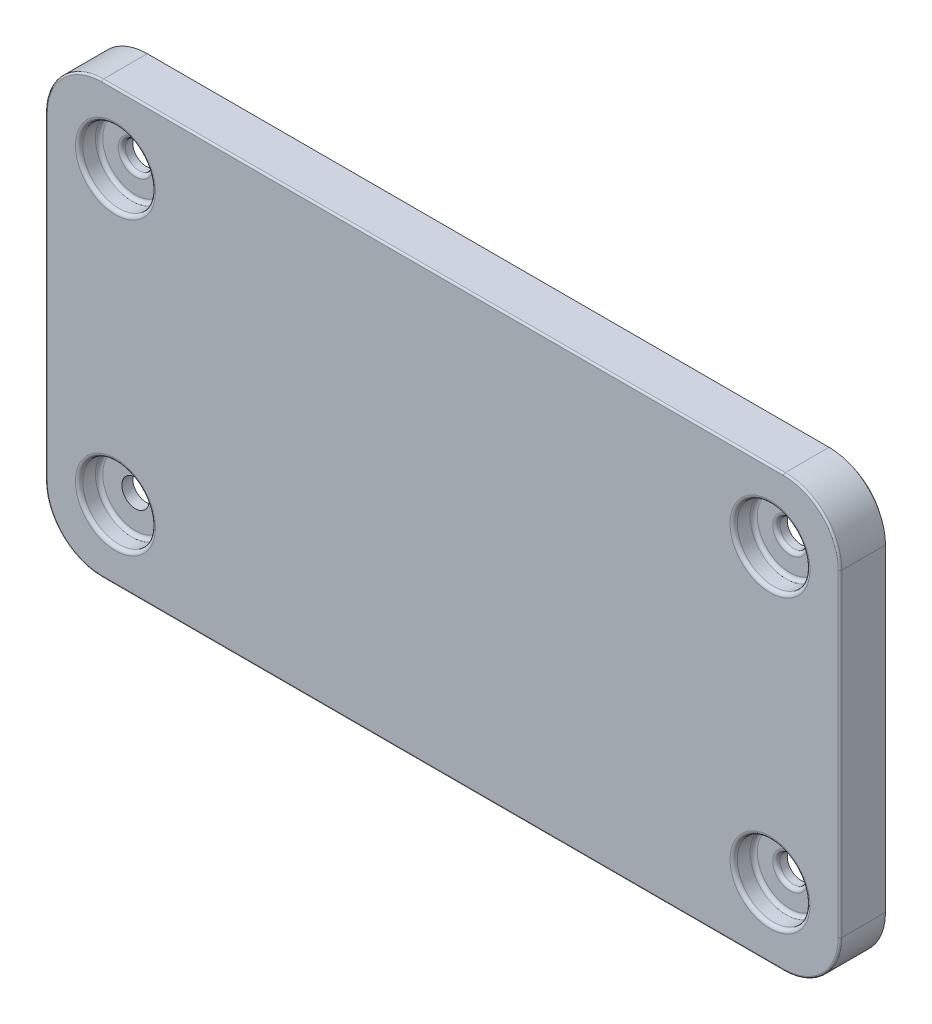
SolidWorks part; units mm, degrees
ref_plane "前视基准面" through (0, 0, 0) normal (0, 0, 1) x (1, 0, 0)
ref_plane "上视基准面" through (0, 0, 0) normal (0, 1, 0) x (1, 0, 0)
ref_plane "右视基准面" through (0, 0, 0) normal (1, 0, 0) x (0, 0, -1)
sketch "草图1" plane through (0, 0, -1.6) normal (0, 0, 1) x (1, 0, 0)
  line L0 (-2.5004, 42.5) -> (-77.4996, 42.5)
  line L1 (-82.5, 37.4996) -> (-82.5, 2.5004)
  line L2 (-77.4996, -2.5) -> (-2.5004, -2.5)
  line L3 (2.5, 2.5004) -> (2.5, 37.4996)
  line L4 (0, 2.5) -> (0, 37.5)
  line L5 (-2.5, 40) -> (-77.5, 40)
  line L6 (-80, 37.5) -> (-80, 2.5)
  line L7 (-77.5, 0) -> (-2.5, 0)
  line L8 (0, 2.5) -> (0, 37.5)
  line L9 (-2.5, 40) -> (-77.5, 40)
  line L10 (-80, 37.5) -> (-80, 2.5)
  line L11 (-77.5, 0) -> (-2.5, 0)
  line L12 (-2.5005, 43.7) -> (-77.4995, 43.7)
  line L13 (-83.7, 37.4995) -> (-83.7, 2.5005)
  line L14 (-77.4995, -3.7) -> (-2.5005, -3.7)
  line L15 (3.7, 2.5005) -> (3.7, 37.4995)
  arc A0 (-77.4996, 42.5) -> (-82.5, 37.4996) centre (-77.5008, 37.5008) ccw
  arc A1 (-82.5, 2.5004) -> (-77.4996, -2.5) centre (-77.5008, 2.4992) ccw
  arc A2 (-2.5004, -2.5) -> (2.5, 2.5004) centre (-2.4992, 2.4992) ccw
  arc A3 (2.5, 37.4996) -> (-2.5004, 42.5) centre (-2.4992, 37.5008) ccw
  arc A4 (0, 37.5) -> (-2.5, 40) centre (-2.4992, 37.5008) ccw
  arc A5 (-77.5, 40) -> (-80, 37.5) centre (-77.5008, 37.5008) ccw
  arc A6 (-80, 2.5) -> (-77.5, 0) centre (-77.5008, 2.4992) ccw
  arc A7 (-2.5, 0) -> (0, 2.5) centre (-2.4992, 2.4992) ccw
  arc A8 (0, 37.5) -> (-2.5, 40) centre (-2.4992, 37.5008) ccw
  arc A9 (-77.5, 40) -> (-80, 37.5) centre (-77.5008, 37.5008) ccw
  arc A10 (-80, 2.5) -> (-77.5, 0) centre (-77.5008, 2.4992) ccw
  arc A11 (-2.5, 0) -> (0, 2.5) centre (-2.4992, 2.4992) ccw
  arc A12 (-77.4995, 43.7) -> (-83.7, 37.4995) centre (-77.5008, 37.5008) ccw
  arc A13 (-83.7, 2.5005) -> (-77.4995, -3.7) centre (-77.5008, 2.4992) ccw
  arc A14 (-2.5005, -3.7) -> (3.7, 2.5005) centre (-2.4992, 2.4992) ccw
  arc A15 (3.7, 37.4995) -> (-2.5005, 43.7) centre (-2.4992, 37.5008) ccw
  dimension "D1" = 0
  dimension "D2" = 2.5
  dimension "D3" = 1.2
extrude "凸台-拉伸1" add sketch "草图1" along normal blind 5 contours A15 L15 A14 L14 A13 L13 A12 L12 L3 A3 L0 A0 L1 A1 L2 A2
sketch "草图3" plane through (0, 0, 3.4) normal (0, 0, 1) x (1, 0, 0)
  line L4 (-2.5005, 43.7) -> (-77.4995, 43.7)
  line L12 (-83.7, 37.4995) -> (-83.7, 2.5005)
  line L16 (-77.4995, -3.7) -> (-2.5005, -3.7)
  line L18 (3.7, 2.5005) -> (3.7, 37.4995)
  line L20 (-2.5005, 43.7) -> (-77.4995, 43.7)
  line L21 (-83.7, 37.4995) -> (-83.7, 2.5005)
  line L22 (-77.4995, -3.7) -> (-2.5005, -3.7)
  line L23 (3.7, 2.5005) -> (3.7, 37.4995)
  arc A4 (3.7, 37.4995) -> (-2.5005, 43.7) centre (-2.4992, 37.5008) ccw
  arc A12 (-77.4995, 43.7) -> (-83.7, 37.4995) centre (-77.5008, 37.5008) ccw
  arc A16 (-83.7, 2.5005) -> (-77.4995, -3.7) centre (-77.5008, 2.4992) ccw
  arc A18 (-2.5005, -3.7) -> (3.7, 2.5005) centre (-2.4992, 2.4992) ccw
  arc A20 (3.7, 37.4995) -> (-2.5005, 43.7) centre (-2.4992, 37.5008) ccw
  arc A21 (-77.4995, 43.7) -> (-83.7, 37.4995) centre (-77.5008, 37.5008) ccw
  arc A22 (-83.7, 2.5005) -> (-77.4995, -3.7) centre (-77.5008, 2.4992) ccw
  arc A23 (-2.5005, -3.7) -> (3.7, 2.5005) centre (-2.4992, 2.4992) ccw
  dimension "D1" = 0
extrude "凸台-拉伸2" add sketch "草图3" against normal blind 1.2
sketch "草图4" plane through (0, 0, 0) normal (0, 0, 1) x (1, 0, 0)
  circle A4 centre (-76, 4) radius 1.5
  circle A5 centre (-4, 4) radius 1.5
  circle A6 centre (-4, 36) radius 1.5
  circle A7 centre (-76, 36) radius 1.5
  circle A8 centre (-76, 36) radius 4
  circle A9 centre (-4, 36) radius 4
  circle A10 centre (-4, 4) radius 4
  circle A11 centre (-76, 4) radius 4
  dimension "D1" = 8
  dimension "D2" = 8
  dimension "D3" = 8
  dimension "D4" = 8
  dimension "D5" = 3
  dimension "D6" = 3
  dimension "D7" = 3
  dimension "D8" = 3
extrude "凸台-拉伸3" add sketch "草图4" along normal blind 1.2 separate body contours A8 A7 | A9 A6 | A11 A4 | A10 A5
sketch "草图5" plane through (0, 0, 0) normal (0, 0, -1) x (-1, 0, 0)
  circle A0 centre (76, 36) radius 4 construction
  circle A1 centre (4, 36) radius 4 construction
  circle A2 centre (4, 4) radius 4 construction
  circle A3 centre (76, 4) radius 4 construction
  circle A4 centre (76, 36) radius 4
  circle A5 centre (4, 36) radius 4
  circle A6 centre (4, 4) radius 4
  circle A7 centre (76, 4) radius 4
  circle A8 centre (76, 4) radius 5.2
  circle A9 centre (4, 4) radius 5.2
  circle A10 centre (4, 36) radius 5.2
  circle A11 centre (76, 36) radius 5.2
  circle M5 centre (76, 4) radius 4
  dimension "D1" = 1.2
extrude "凸台-拉伸4" add sketch "草图5" against normal up to next contours A8 M5 | A9 A6 | A10 A5 | A11 A4
sketch "草图6" plane through (0, 0, 1.2) normal (0, 0, 1) x (1, 0, 0)
  circle A0 centre (-76, 4) radius 4 construction
  circle A1 centre (-4, 4) radius 4 construction
  circle A2 centre (-4, 36) radius 4 construction
  circle A3 centre (-76, 36) radius 4 construction
  circle A4 centre (-76, 4) radius 4
  circle A5 centre (-4, 4) radius 4
  circle A6 centre (-4, 36) radius 4
  circle A7 centre (-76, 36) radius 4
extrude "切除-拉伸1" cut sketch "草图6" along normal through all
sketch "草图7" plane through (0, 0, -1.6) normal (0, 0, -1) x (-1, 0, 0)
  line L0 (2.5004, -2.9) -> (77.4996, -2.9)
  line L1 (82.9, 2.5004) -> (82.9, 37.4996)
  line L2 (77.4996, 42.9) -> (2.5004, 42.9)
  line L3 (-2.9, 37.4996) -> (-2.9, 2.5004)
  line L4 (-2.5, 37.4996) -> (-2.5, 2.5004)
  line L5 (2.5004, -2.5) -> (77.4996, -2.5)
  line L6 (82.5, 2.5004) -> (82.5, 37.4996)
  line L7 (77.4996, 42.5) -> (2.5004, 42.5)
  line L8 (-2.5, 37.4996) -> (-2.5, 2.5004)
  line L9 (2.5004, -2.5) -> (77.4996, -2.5)
  line L10 (82.5, 2.5004) -> (82.5, 37.4996)
  line L11 (77.4996, 42.5) -> (2.5004, 42.5)
  arc A0 (77.4996, -2.9) -> (82.9, 2.5004) centre (77.5008, 2.4992) ccw
  arc A1 (82.9, 37.4996) -> (77.4996, 42.9) centre (77.5008, 37.5008) ccw
  arc A2 (2.5004, 42.9) -> (-2.9, 37.4996) centre (2.4992, 37.5008) ccw
  arc A3 (-2.9, 2.5004) -> (2.5004, -2.9) centre (2.4992, 2.4992) ccw
  arc A4 (-2.5, 2.5004) -> (2.5004, -2.5) centre (2.4992, 2.4992) ccw
  arc A5 (77.4996, -2.5) -> (82.5, 2.5004) centre (77.5008, 2.4992) ccw
  arc A6 (82.5, 37.4996) -> (77.4996, 42.5) centre (77.5008, 37.5008) ccw
  arc A7 (2.5004, 42.5) -> (-2.5, 37.4996) centre (2.4992, 37.5008) ccw
  arc A8 (-2.5, 2.5004) -> (2.5004, -2.5) centre (2.4992, 2.4992) ccw
  arc A9 (77.4996, -2.5) -> (82.5, 2.5004) centre (77.5008, 2.4992) ccw
  arc A10 (82.5, 37.4996) -> (77.4996, 42.5) centre (77.5008, 37.5008) ccw
  arc A11 (2.5004, 42.5) -> (-2.5, 37.4996) centre (2.4992, 37.5008) ccw
  line M17 (-2.5, 2.5004) -> (-2.5, 37.4996)
  arc M18 (-2.5, 37.4996) -> (2.5004, 42.5) centre (2.4992, 37.5008) cw
  line M19 (2.5004, 42.5) -> (77.4996, 42.5)
  arc M20 (77.4996, 42.5) -> (82.5, 37.4996) centre (77.5008, 37.5008) cw
  line M21 (82.5, 37.4996) -> (82.5, 2.5004)
  arc M22 (82.5, 2.5004) -> (77.4996, -2.5) centre (77.5008, 2.4992) cw
  line M23 (77.4996, -2.5) -> (2.5004, -2.5)
  arc M24 (2.5004, -2.5) -> (-2.5, 2.5004) centre (2.4992, 2.4992) cw
  dimension "D1" = 0
  dimension "D2" = 0.4
extrude "凸台-拉伸5" add sketch "草图7" along normal blind 0.6 contours L3 A3 L0 A0 L1 A1 L2 A2 M24 M17 M18 M19 M20 M21 M22 M23
sketch "草图8" plane through (0, 42.9, 0) normal (0, 1, 0) x (1, 0, 0)
  line L0 (-2.5005, 1.6) -> (-77.4995, 1.6) construction
  line L1 (-32.0218, 1.6) -> (-39.9618, 1.6)
  line L2 (-32.0218, 1.6) -> (-32.0218, 2.2)
  line L3 (-32.0218, 2.2) -> (-39.9618, 2.2)
  line L4 (-39.9618, 1.6) -> (-39.9618, 2.2)
  line L5 (-32.0218, 9.6662) -> (-32.0218, 1.6) construction
  line L6 (-77.4996, 2.2) -> (-2.5004, 2.2) construction
  line L7 (-39.9618, 9.6662) -> (-39.9618, 1.6) construction
extrude "切除-拉伸2" cut sketch "草图8" against normal up to next
sketch "草图9" plane through (0, -3.7, 0) normal (0, -1, 0) x (1, 0, 0)
  line L0 (-77.4995, -1.6) -> (-2.5005, -1.6) construction
  line L1 (-7.574, -1.6) -> (-18.334, -1.6)
  line L2 (-7.574, -1.6) -> (-7.574, -2.2)
  line L3 (-7.574, -2.2) -> (-18.334, -2.2)
  line L4 (-18.334, -1.6) -> (-18.334, -2.2)
  line L5 (-7.574, -7) -> (-7.574, -1.6) construction
  line L6 (-18.334, -1.6) -> (-18.334, -7) construction
  line L7 (-2.5004, -2.2) -> (-77.4996, -2.2) construction
  line L8 (-34.0027, -7) -> (-34.0027, -1.6) construction
  line L9 (-34.0027, -1.6) -> (-44.7627, -1.6)
  line L10 (-34.0027, -1.6) -> (-34.0027, -2.2)
  line L11 (-34.0027, -2.2) -> (-44.7627, -2.2)
  line L12 (-44.7627, -1.6) -> (-44.7627, -2.2)
  line L13 (-44.7627, -1.6) -> (-44.7627, -7) construction
  line L14 (-60.4314, -7) -> (-60.4314, -1.6) construction
  line L15 (-60.4314, -1.6) -> (-71.1914, -1.6)
  line L16 (-60.4314, -1.6) -> (-60.4314, -2.2)
  line L17 (-60.4314, -2.2) -> (-71.1914, -2.2)
  line L18 (-71.1914, -1.6) -> (-71.1914, -2.2)
  line L19 (-71.1914, -1.6) -> (-71.1914, -7) construction
  line M2 (-77.4995, -1.6) -> (-2.5005, -1.6)
extrude "切除-拉伸3" cut sketch "草图9" against normal up to next contours L4 L3 L2 M2 | L12 L11 L10 M2 | L18 L17 L16 M2
sketch "草图10" plane through (0, -2.5, 0) normal (0, 1, 0) x (1, 0, 0)
  line L1 (-7.574, 1.6) -> (-18.334, 1.6)
  line L3 (-7.574, 1.2) -> (-18.334, 1.2)
  line L5 (-34.0027, 1.6) -> (-44.7627, 1.6)
  line L6 (-34.0027, 1.6) -> (-34.0027, 1.2)
  line L7 (-34.0027, 1.2) -> (-44.7627, 1.2)
  line L9 (-71.1914, 1.6) -> (-60.4314, 1.6)
  line L10 (-34.0027, 1.6) -> (-33.6027, 1.6)
  line L11 (-34.0027, 1.6) -> (-34.0027, 1.2)
  line L12 (-34.0027, 1.2) -> (-33.6027, 1.2)
  line L13 (-33.6027, 1.6) -> (-33.6027, 1.2)
  line L14 (-44.7627, 1.6) -> (-45.1627, 1.6)
  line L15 (-44.7627, 1.6) -> (-44.7627, 1.2)
  line L16 (-44.7627, 1.2) -> (-45.1627, 1.2)
  line L17 (-45.1627, 1.6) -> (-45.1627, 1.2)
  line L18 (-7.574, 1.6) -> (-7.174, 1.6)
  line L19 (-7.574, 1.6) -> (-7.574, 1.2)
  line L20 (-7.574, 1.2) -> (-7.174, 1.2)
  line L21 (-7.174, 1.6) -> (-7.174, 1.2)
  line L22 (-18.334, 1.6) -> (-18.734, 1.6)
  line L23 (-18.334, 1.6) -> (-18.334, 1.2)
  line L24 (-18.334, 1.2) -> (-18.734, 1.2)
  line L25 (-18.734, 1.6) -> (-18.734, 1.2)
  line L26 (-71.1914, 1.6) -> (-71.1914, 1.2)
  line L27 (-71.1914, 1.2) -> (-60.4314, 1.2)
  line L28 (-60.4314, 1.6) -> (-60.4314, 1.2)
  line L29 (-60.4314, 1.6) -> (-60.0314, 1.6)
  line L30 (-60.4314, 1.6) -> (-60.4314, 1.2)
  line L31 (-60.4314, 1.2) -> (-60.0314, 1.2)
  line L32 (-60.0314, 1.6) -> (-60.0314, 1.2)
  line L33 (-71.1914, 1.6) -> (-71.5914, 1.6)
  line L34 (-71.1914, 1.6) -> (-71.1914, 1.2)
  line L35 (-71.1914, 1.2) -> (-71.5914, 1.2)
  line L36 (-71.5914, 1.6) -> (-71.5914, 1.2)
  line M12 (-34.0027, 1.6) -> (-44.7627, 1.6)
  line M20 (-7.574, 1.6) -> (-18.334, 1.6)
  dimension "D1" = 0.4
  dimension "D2" = 0.4
  dimension "D3" = 0.4
  dimension "D4" = 0.4
  dimension "D5" = 0.4
  dimension "D6" = 0.4
  dimension "D7" = 0.4
  dimension "D8" = 0.4
  dimension "D9" = 0.4
extrude "凸台-拉伸6" add sketch "草图10" along normal offset from surface (2.1 mm away) 0.4 contours L23 L3 L19 M20 | L22 L25 L24 L23 | L21 L18 L19 L20 | L15 L7 L6 M12 | L14 L17 L16 L15 | L13 L10 L6 L12 | L26 L9 L28 L27 | L30 L29 L32 L31 | L34 L33 L36 L35
sketch "草图11" plane through (0, 42.5, 0) normal (0, -1, 0) x (-1, 0, 0)
  line L0 (32.0218, 1.6) -> (32.0218, 2.2) construction
  line L1 (39.9618, 1.6) -> (32.0218, 1.6)
  line L2 (39.9618, 1.6) -> (39.9618, 1.2)
  line L3 (39.9618, 1.2) -> (32.0218, 1.2)
  line L4 (32.0218, 1.6) -> (32.0218, 1.2)
  line L6 (32.0218, 1.2) -> (31.6218, 1.2)
  line L7 (32.0218, 1.2) -> (32.0218, 1.6)
  line L8 (32.0218, 1.6) -> (31.6218, 1.6)
  line L9 (31.6218, 1.2) -> (31.6218, 1.6)
  line L10 (39.9618, 1.2) -> (40.3618, 1.2)
  line L11 (39.9618, 1.2) -> (39.9618, 1.6)
  line L12 (39.9618, 1.6) -> (40.3618, 1.6)
  line L13 (40.3618, 1.2) -> (40.3618, 1.6)
  line M14 (39.9618, 1.6) -> (32.0218, 1.6)
  dimension "D1" = 0.4
  dimension "D2" = 0.4
  dimension "D3" = 0.4
extrude "凸台-拉伸7" add sketch "草图11" along normal offset from surface (2.1 mm away) 0.4 contours L4 L3 L2 M14 | L10 L13 L12 L2 | L9 L6 L4 L8
fillet "圆角1" radius 0.4 19 edges at (0, 4, 3.4) (0, 4, 1.2) (-2.5, 4, 1.2) (0, 36, 1.2) (-2.5, 36, 1.2) (0, 36, 3.4) (-74.5, 36, 1.2) (-72, 36, 3.4) (-72, 36, 1.2) (-72, 4, 3.4) (-72, 4, 1.2) (-81.2, 4, 0) (-70.8, 4, 2.2) (-70.8, 36, 2.2) (-81.2, 36, 0) (-9.2, 36, 0) (1.2, 36, 2.2) (1.2, 4, 2.2) (-9.2, 4, 0)
fillet "圆角2" radius 1.5 4 edges at (-35.9918, 42.5, -1.2) (-12.954, -2.5, -1.2) (-39.3827, -2.5, -1.2) (-65.8114, -2.5, -1.2)
fillet "圆角3" radius 0.2 16 edges at (-40, 43.7, 3.4) (1.8843, 41.8843, 3.4) (3.7, 20, 3.4) (1.8843, -1.8843, 3.4) (-40, -3.7, 3.4) (-81.8843, -1.8843, 3.4) (-83.7, 20, 3.4) (-81.0358, 41.0358, 2.2) (-40, 42.5, 2.2) (1.0358, 41.0358, 2.2) (2.5, 20, 2.2) (1.0358, -1.0358, 2.2) (-40, -2.5, 2.2) (-81.0358, -1.0358, 2.2) (-81.8843, 41.8843, 3.4) (-82.5, 20, 2.2)
sketch "草图12" plane through (0, 0, -2.2) normal (0, 0, -1) x (-1, 0, 0)
  line L0 (77.4995, -3.7) -> (2.5005, -3.7) construction
  line L1 (2.5005, 43.7) -> (77.4995, 43.7) construction
  line L2 (44.7627, -2.9) -> (60.4314, -2.9) construction
  line L3 (44.7627, -2.5) -> (44.7627, -2.9) construction
  line L4 (34.0027, -2.5) -> (34.0027, -2.9) construction
  line L5 (18.334, -2.9) -> (34.0027, -2.9) construction
  line L6 (18.334, -2.5) -> (18.334, -2.9) construction
  line L7 (7.574, -2.5) -> (7.574, -2.9) construction
  line L8 (2.5004, -2.9) -> (7.574, -2.9) construction
  line L9 (32.0218, 42.9) -> (2.5004, 42.9) construction
  line L10 (32.0218, 42.5) -> (32.0218, 42.9) construction
  line L11 (77.4996, 42.9) -> (39.9618, 42.9) construction
  line L12 (39.9618, 42.5) -> (39.9618, 42.9) construction
  line L13 (44.7627, -2.9) -> (60.4314, -2.9)
  line L14 (44.7627, -2.5) -> (44.7627, -2.9)
  line L15 (34.0027, -2.5) -> (34.0027, -2.9)
  line L16 (18.334, -2.9) -> (34.0027, -2.9)
  line L17 (18.334, -2.5) -> (18.334, -2.9)
  line L18 (7.574, -2.5) -> (7.574, -2.9)
  line L19 (2.5004, -2.9) -> (7.574, -2.9)
  line L20 (32.0218, 42.9) -> (2.5004, 42.9)
  line L21 (32.0218, 42.5) -> (32.0218, 42.9)
  line L22 (77.4996, 42.9) -> (39.9618, 42.9)
  line L23 (39.9618, 42.5) -> (39.9618, 42.9)
  line L24 (60.4314, -2.5) -> (60.4314, -2.9) construction
  line L25 (60.4314, -2.5) -> (60.4314, -2.9)
  circle A0 centre (72.3914, -2.5) radius 1.2
  circle A7 centre (30.8218, 42.5) radius 1.2
  circle A8 centre (59.2314, -2.5) radius 1.2
  circle A9 centre (45.9627, -2.5) radius 1.2
  circle A10 centre (32.8027, -2.5) radius 1.2
  circle A11 centre (19.534, -2.5) radius 1.2
  circle A12 centre (6.374, -2.5) radius 1.2
  circle A13 centre (41.1618, 42.5) radius 1.2
  line M3 (71.1914, -2.5) -> (71.1914, -2.9)
  line M4 (71.1914, -2.9) -> (77.4996, -2.9)
  line M8 (77.4996, 42.9) -> (39.9618, 42.9)
  line M9 (39.9618, 42.9) -> (39.9618, 42.5)
  dimension "D1" = 2.4
  dimension "D2" = 2.4
  dimension "D3" = 2.4
  dimension "D4" = 2.4
  dimension "D5" = 2.4
  dimension "D6" = 2.4
  dimension "D7" = 2.4
  dimension "D8" = 2.4
extrude "切除-拉伸4" cut sketch "草图12" against normal up to surface (0.6 mm away) contours A0 M3 M4 | A8 L13 L25 | A9 L14 L13 | A10 L16 L15 | A11 L17 L16 | A12 L19 L18 | A13 M8 M9 | A7 L21 L20 up to face at (-38.828, 11.17, -1.6)
